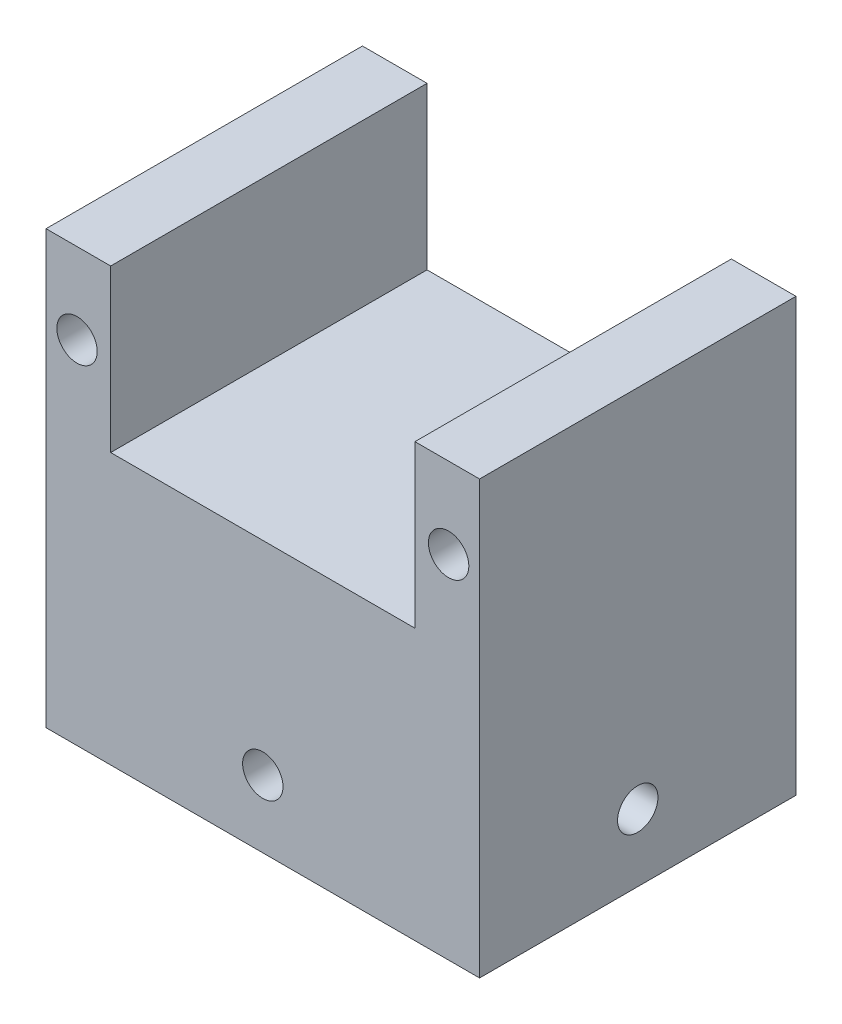
SolidWorks part; units mm, degrees
ref_plane "Front Plane" through (0, 0, 0) normal (0, 0, 1) x (1, 0, 0)
ref_plane "Top Plane" through (0, 0, 0) normal (0, 1, 0) x (1, 0, 0)
ref_plane "Right Plane" through (0, 0, 0) normal (1, 0, 0) x (0, 0, -1)
sketch "Sketch1" plane through (0, 0, 0) normal (0, 1, 0) x (1, 0, 0)
  line L1 (-10.869, 9.5321) -> (21.331, 9.5321)
  line L2 (-10.869, 9.5321) -> (-10.869, -13.9679)
  line L3 (-10.869, -13.9679) -> (21.331, -13.9679)
  line L4 (21.331, 9.5321) -> (21.331, -13.9679)
  dimension "D1" = 32.2
  dimension "D2" = 23.5
extrude "Boss-Extrude1" add sketch "Sketch1" along normal blind 32.1
sketch "Sketch2" plane through (0, 0, -9.5321) normal (0, 0, -1) x (-1, 0, 0)
  line L0 (-21.331, 32.1) -> (10.869, 32.1) construction
  line L1 (-16.531, 32.1) -> (6.069, 32.1)
  line L2 (-16.531, 32.1) -> (-16.531, 20.1)
  line L3 (-16.531, 20.1) -> (6.069, 20.1)
  line L4 (6.069, 32.1) -> (6.069, 20.1)
  line L5 (-5.231, 20.1) -> (-5.231, 15.2123) construction
  line L6 (-21.331, 0) -> (10.869, 0) construction
  circle A0 centre (8.569, 26.1) radius 1.5
  circle A1 centre (-19.031, 26.1) radius 1.5
  circle A2 centre (-5.231, 5) radius 1.5
  point P8 (-5.231, 0)
  point P17 (-5.231, 0)
  dimension "D4" = 3
  dimension "D5" = 3
  dimension "D6" = 2.5
  dimension "D7" = 2.5
  dimension "D8" = 5
  dimension "D9" = 3
  dimension "D1" = 22.6
  dimension "D2" = 0
  dimension "D3" = 12
extrude "Cut-Extrude1" cut sketch "Sketch2" against normal blind 32.1
sketch "Sketch3" plane through (-10.869, 0, 0) normal (-1, 0, 0) x (0, 0, 1)
  line L0 (-9.5321, 0) -> (13.9679, 0) construction
  circle A0 centre (2.2179, 5) radius 1.5
  point P2 (2.2179, 0)
  dimension "D1" = 3
  dimension "D2" = 5
extrude "Cut-Extrude2" cut sketch "Sketch3" against normal blind 36.1
